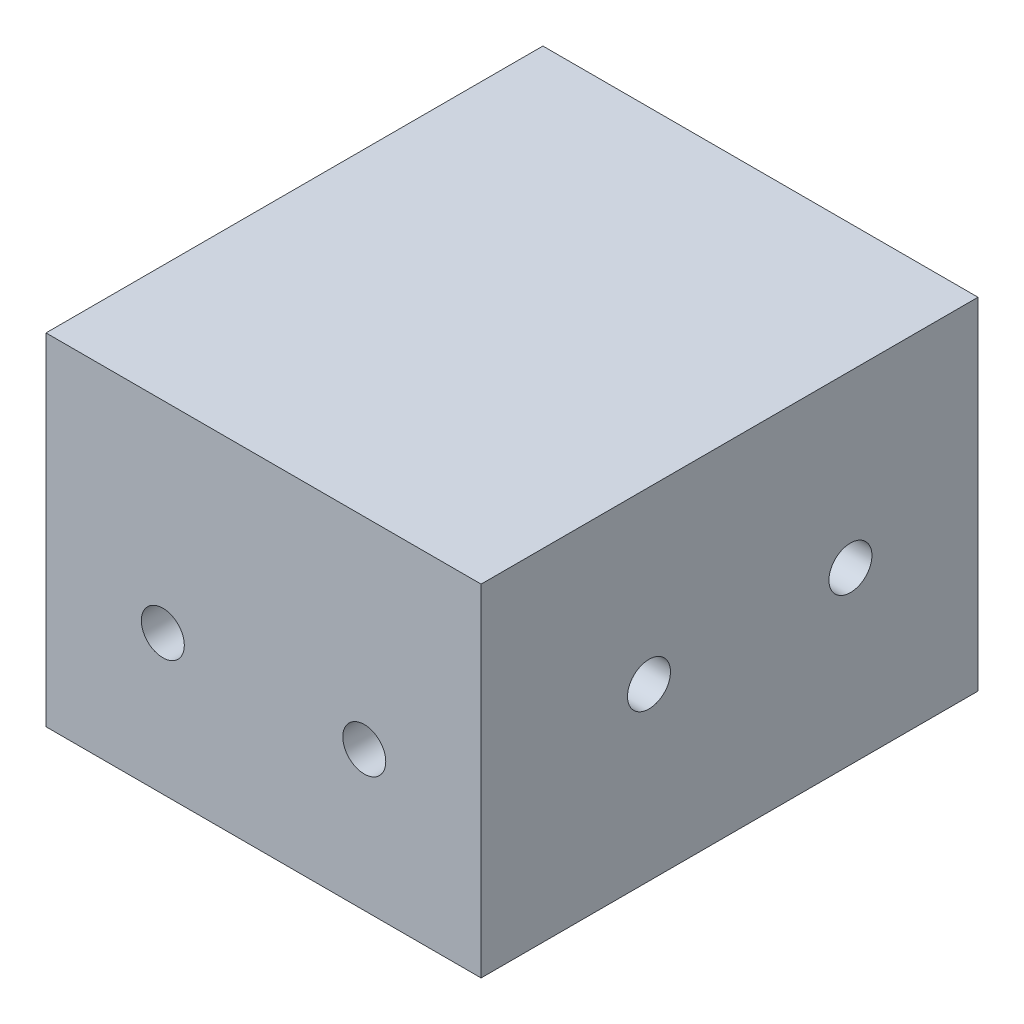
SolidWorks part; units mm, degrees
ref_plane "Front Plane" through (0, 0, 0) normal (0, 0, 1) x (1, 0, 0)
ref_plane "Top Plane" through (0, 0, 0) normal (0, 1, 0) x (1, 0, 0)
ref_plane "Right Plane" through (0, 0, 0) normal (1, 0, 0) x (0, 0, -1)
sketch "Sketch1" plane through (0, 0, 0) normal (0, 0, 1) x (1, 0, 0)
  line L1 (0, 0) -> (32.4, 0)
  line L2 (0, 0) -> (0, 25.4)
  line L3 (0, 25.4) -> (32.4, 25.4)
  line L4 (32.4, 0) -> (32.4, 25.4)
  dimension "D1" = 25.4
  dimension "D2" = 32.4
extrude "Boss-Extrude1" add sketch "Sketch1" along normal blind 35
shell "Shell1" thickness 4
sketch "Sketch2" plane through (32.4, 0, 0) normal (1, 0, 0) x (0, 0, -1)
  line L0 (-24.5, 12.7) -> (-9.5, 12.7) construction
  line L1 (-35, 25.4) -> (0, 25.4) construction
  line L2 (-35, 0) -> (0, 0) construction
  line L3 (-35, 0) -> (-35, 25.4) construction
  circle A0 centre (-24.5, 12.7) radius 1.6
  circle A1 centre (-9.5, 12.7) radius 1.6
  point P10 (-50, 10.6378)
  dimension "D1" = 3.2
  dimension "D2" = 3.2
  dimension "D3" = 15
  dimension "D4" = 10.5
extrude "Cut-Extrude1" cut sketch "Sketch2" against normal through all
sketch "Sketch3" plane through (0, 0, 35) normal (0, 0, 1) x (1, 0, 0)
  line L0 (8.7, 10.4) -> (23.7, 10.4) construction
  line L1 (32.4, 25.4) -> (0, 25.4) construction
  line L3 (16.2, 25.4) -> (16.2, 0) construction
  line L4 (0, 0) -> (32.4, 0) construction
  circle A0 centre (8.7, 10.4) radius 1.6
  circle A1 centre (23.7, 10.4) radius 1.6
  dimension "D1" = 3.2
  dimension "D2" = 3.2
  dimension "D3" = 15
  dimension "D5" = 15
extrude "Cut-Extrude2" cut sketch "Sketch3" against normal up to next
sketch "Sketch4" plane through (0, 0, 31) normal (0, 0, -1) x (-1, 0, 0)
  line L1 (-10.2877, 13.15) -> (-11.8754, 10.4)
  line L2 (-11.8754, 10.4) -> (-10.2877, 7.65)
  line L3 (-10.2877, 7.65) -> (-7.1123, 7.65)
  line L4 (-7.1123, 7.65) -> (-5.5246, 10.4)
  line L5 (-5.5246, 10.4) -> (-7.1123, 13.15)
  line L6 (-7.1123, 13.15) -> (-10.2877, 13.15)
  line L7 (-25.2877, 13.15) -> (-26.8754, 10.4)
  line L8 (-26.8754, 10.4) -> (-25.2877, 7.65)
  line L9 (-25.2877, 7.65) -> (-22.1123, 7.65)
  line L10 (-22.1123, 7.65) -> (-20.5246, 10.4)
  line L11 (-20.5246, 10.4) -> (-22.1123, 13.15)
  line L12 (-22.1123, 13.15) -> (-25.2877, 13.15)
  circle A0 centre (-8.7, 10.4) radius 2.75 construction
  circle A1 centre (-23.7, 10.4) radius 2.75 construction
  dimension "D1" = 5.5
  dimension "D2" = 5.5
extrude "Cut-Extrude3" cut sketch "Sketch4" against normal blind 2
ref_plane "Plane1" through (0, 0, 35) normal (1, 0, 0) x (0, 0, -1)
sketch "Sketch7" plane through (0, 0, 35) normal (0, 0, 1) x (1, 0, 0)
  line L4 (0, 25.4) -> (0, 0)
  line L5 (0, 0) -> (32.4, 0)
  line L6 (32.4, 0) -> (32.4, 25.4)
  line L7 (32.4, 25.4) -> (0, 25.4)
  line L8 (0, 25.4) -> (0, 0)
  line L9 (0, 0) -> (32.4, 0)
  line L10 (32.4, 0) -> (32.4, 25.4)
  line L11 (32.4, 25.4) -> (0, 25.4)
  circle A0 centre (8.7, 10.4) radius 1.6 construction
  circle A1 centre (23.7, 10.4) radius 1.6 construction
  circle A2 centre (8.7, 10.4) radius 1.6
  circle A3 centre (23.7, 10.4) radius 1.6
  dimension "D1" = 0
extrude "Boss-Extrude2" add sketch "Sketch7" along normal blind 2 contours L11 L8 L9 L10 | A2 | A3
equation "\"D2@Sketch2\"=\"D1@Sketch2\""
equation "\"D2@Sketch3\"=\"D1@Sketch3\""
equation "\"D2@Sketch4\"=\"D1@Sketch4\""
